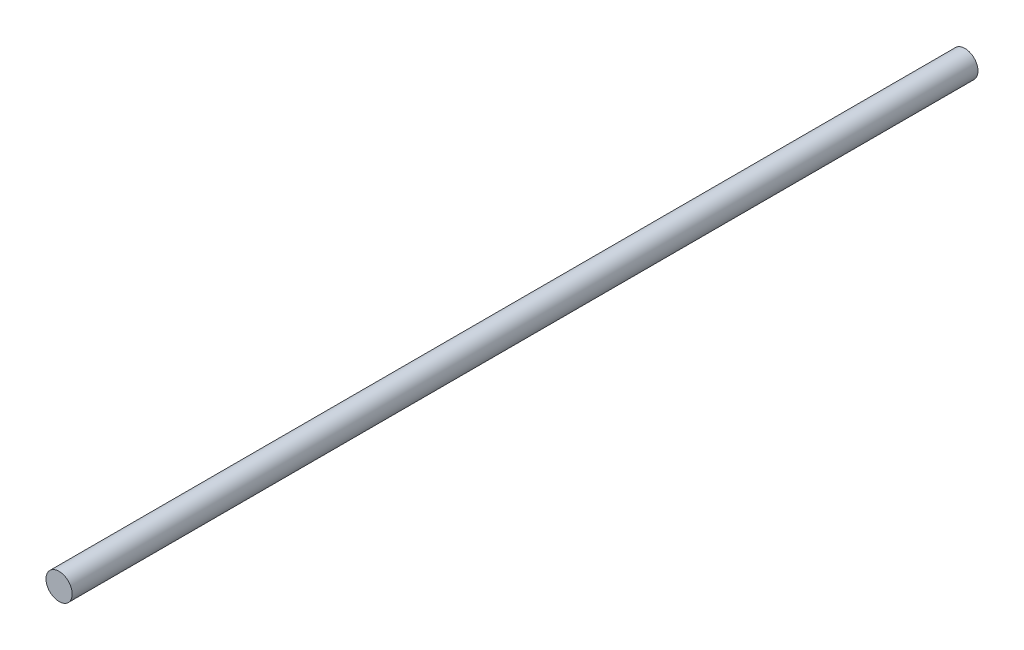
SolidWorks part; units mm, degrees
ref_plane "Front Plane" through (0, 0, 0) normal (0, 0, 1) x (1, 0, 0)
ref_plane "Top Plane" through (0, 0, 0) normal (0, 1, 0) x (1, 0, 0)
ref_plane "Right Plane" through (0, 0, 0) normal (1, 0, 0) x (0, 0, -1)
sketch "Sketch1" plane through (0, 0, 0) normal (0, 0, 1) x (1, 0, 0)
  circle A0 centre (0, 0) radius 6
  dimension "D1" = 12
extrude "Boss-Extrude1" add sketch "Sketch1" along normal blind 414.6
